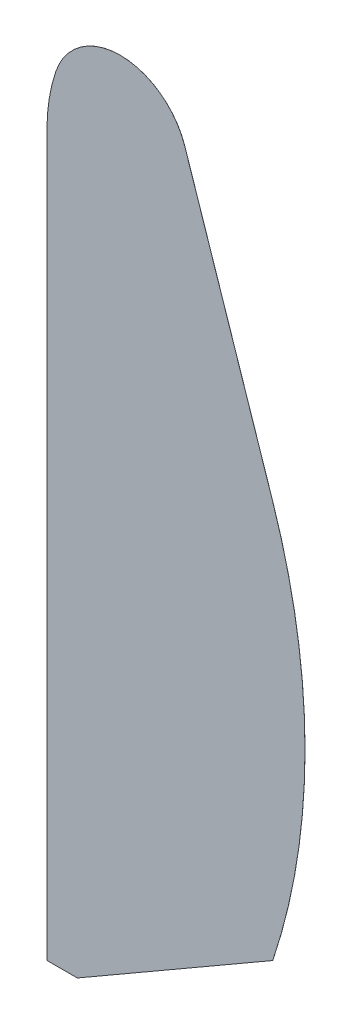
SolidWorks part; units mm, degrees
ref_plane "Front Plane" through (0, 0, 0) normal (1, 0, 0) x (0, 1, 0)
ref_plane "Top Plane" through (0, 0, 0) normal (0, 0, 1) x (0, 1, 0)
ref_plane "Right Plane" through (0, 0, 0) normal (0, 1, 0) x (-1, 0, 0)
sketch "Sketch1" plane through (0, 0, 0) normal (0, 0, 1) x (0, 1, 0)
  line L0 (0, 0) -> (0, 50000) construction
  line L1 (0, 0) -> (50000, 0) construction
  line L2 (143.5634, 601.065) -> (1381.2364, 932.6984) construction
  line L3 (0, 0) -> (118.575, 0)
  line L4 (0, 0) -> (0, -5)
  line L5 (0, -5) -> (18.5835, -37.1875)
  line L6 (127.5, -22.6986) -> (84.0434, -37.1875)
  line L7 (0, 0) -> (51.3134, -42.5)
  line L8 (0, 0) -> (127.5, -22.6986)
  arc A0 (118.575, 0) -> (127.5, -1.4486) centre (118.575, -28.2175) cw
  arc A1 (127.5, -1.4486) -> (127.5, -22.6986) centre (123.9575, -12.0736) cw
  arc A2 (18.5835, -37.1875) -> (84.0434, -37.1875) centre (51.3134, 60.9799) ccw
  dimension "D1" = 5
  dimension "D2" = 37.1875
  dimension "D3" = 118.575
  dimension "Span" = 127.5
  dimension "Chord" = 42.5
  dimension "D4" = 30
  dimension "D5" = 21.25
extrude "Boss-Extrude1" add sketch "Sketch1" along normal blind 0.01 contours L6 A2 L5 L4 L3 A0 A1
equation "\"D3@Sketch1\"=\"Span@Sketch1\"*0.93"
equation "\"D2@Sketch1\"=\"Chord@Sketch1\"*0.875"
equation "\"Chord@Sketch1\"=\"Span@Sketch1\"/3"
equation "\"D5@Sketch1\"=\"Chord@Sketch1\"/2"
